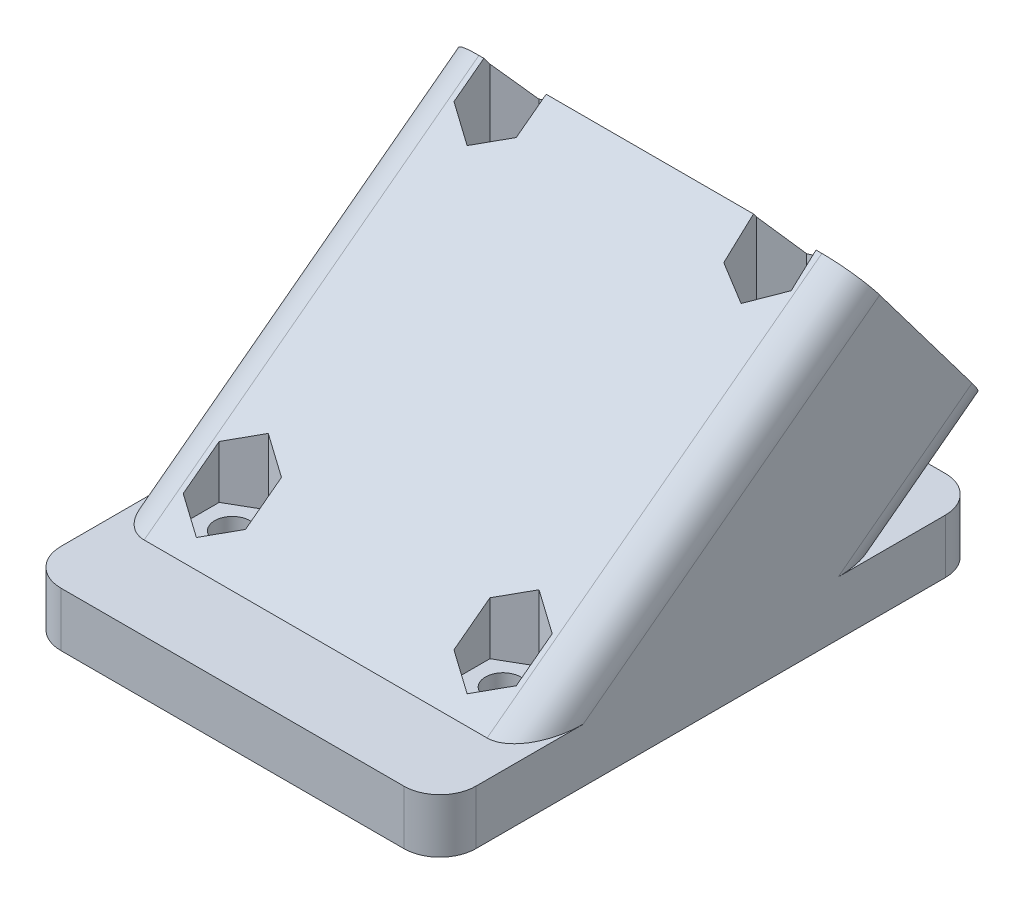
SolidWorks part; units mm, degrees
ref_plane "Front Plane" through (0, 0, 0) normal (0, 0, 1) x (1, 0, 0)
ref_plane "Top Plane" through (0, 0, 0) normal (0, 1, 0) x (1, 0, 0)
ref_plane "Right Plane" through (0, 0, 0) normal (1, 0, 0) x (0, 0, -1)
sketch "Sketch3" plane through (0, 0, 0) normal (1, 0, 0) x (0, 0, -1)
  line L0 (31.3688, 7.9864) -> (20.7705, 0)
  line L1 (31.3688, 7.9864) -> (16.3234, 27.9522)
  line L2 (30, 0) -> (-30, 0) construction
  line L3 (20.7705, 0) -> (30, 0)
  line L4 (30, 0) -> (30, -6)
  line L5 (30, -6) -> (-30, -6)
  line L6 (-30, -6) -> (-30, 0)
  line L7 (16.3234, 27.9522) -> (-20.7705, 0)
  line L8 (-20.7705, 0) -> (-30, 0)
  line L9 (30, 0) -> (37.3869, 0) construction
  line L10 (37.3869, 0) -> (31.3688, 7.9864) construction
  point P0 (0, 0)
  dimension "D1" = 60
  dimension "D2" = 10
  dimension "D3" = 25
  dimension "D4" = 6
  dimension "D5" = 37
extrude "Boss-Extrude1" add sketch "Sketch3" along normal mid plane 46
sketch "Sketch4" plane through (0, -6, 0) normal (0, -1, 0) x (-1, 0, 0)
  line L1 (15, 15) -> (-15, 15) construction
  line L2 (15, 15) -> (15, -15) construction
  line L3 (15, -15) -> (-15, -15) construction
  line L4 (-15, 15) -> (-15, -15) construction
  line L5 (15, 15) -> (-15, -15) construction
  line L6 (15, -15) -> (-15, 15) construction
  circle A0 centre (15, 15) radius 1.95
  circle A1 centre (15, -15) radius 1.95
  circle A2 centre (-15, -15) radius 1.95
  circle A3 centre (-15, 15) radius 1.95
  point P0 (0, 0)
  dimension "D2" = 3.9
  dimension "D1" = 30
extrude "Cut-Extrude1" cut sketch "Sketch4" against normal up to next
sketch "Sketch6" plane through (0, -6, 0) normal (0, -1, 0) x (-1, 0, 0)
  line L0 (-15, -18.9837) -> (-18.45, -16.9919)
  line L1 (-18.45, -16.9919) -> (-18.45, -13.0081)
  line L2 (-18.45, -13.0081) -> (-15, -11.0163)
  line L3 (-15, -11.0163) -> (-11.55, -13.0081)
  line L4 (-11.55, -13.0081) -> (-11.55, -16.9919)
  line L5 (-11.55, -16.9919) -> (-15, -18.9837)
  line L6 (18.45, -16.9919) -> (18.45, -13.0081)
  line L7 (18.45, -13.0081) -> (15, -11.0163)
  line L8 (15, -11.0163) -> (11.55, -13.0081)
  line L9 (11.55, -13.0081) -> (11.55, -16.9919)
  line L10 (11.55, -16.9919) -> (15, -18.9837)
  line L11 (15, -18.9837) -> (18.45, -16.9919)
  line L12 (15, 11.0163) -> (18.45, 13.0081)
  line L13 (18.45, 13.0081) -> (18.45, 16.9919)
  line L14 (18.45, 16.9919) -> (15, 18.9837)
  line L15 (15, 18.9837) -> (11.55, 16.9919)
  line L16 (11.55, 16.9919) -> (11.55, 13.0081)
  line L17 (11.55, 13.0081) -> (15, 11.0163)
  line L18 (-11.7331, 12.7202) -> (-11.3922, 16.6893)
  line L19 (-11.3922, 16.6893) -> (-14.6591, 18.9691)
  line L20 (-14.6591, 18.9691) -> (-18.2669, 17.2798)
  line L21 (-18.2669, 17.2798) -> (-18.6078, 13.3107)
  line L22 (-18.6078, 13.3107) -> (-15.3409, 11.0309)
  line L23 (-15.3409, 11.0309) -> (-11.7331, 12.7202)
  circle A0 centre (-15, -15) radius 3.9837 construction
  circle A1 centre (15, -15) radius 3.9837 construction
  circle A2 centre (15, 15) radius 3.9837 construction
  circle A3 centre (-15, 15) radius 3.9837 construction
  dimension "D1" = 6.9
extrude "Cut-Extrude3" cut sketch "Sketch6" against normal up to next from offset 6 offset against normal yes
sketch "Sketch7" plane through (0, 17.9693, -23.8461) normal (0, 0.6018, -0.7986) x (-1, 0, 0)
  circle A0 centre (0, 0) radius 2.75
  dimension "D1" = 5.5
extrude "Cut-Extrude4" cut sketch "Sketch7" against normal up to next
sketch "Sketch8" plane through (0, 17.9693, -23.8461) normal (0, 0.6018, -0.7986) x (-1, 0, 0)
  circle A0 centre (0, 0) radius 5
  dimension "D1" = 10
extrude "Cut-Extrude5" cut sketch "Sketch8" against normal up to next from offset 20 offset against normal yes
fillet "Fillet1" radius 4 8 edges at (23, 13.9761, 2.2236) (-23, 13.9761, 2.2236) (-23, 3.9932, -26.0696) (23, 3.9932, -26.0696) (23, -3, 30) (-23, -3, 30) (23, -3, -30) (-23, -3, -30)
